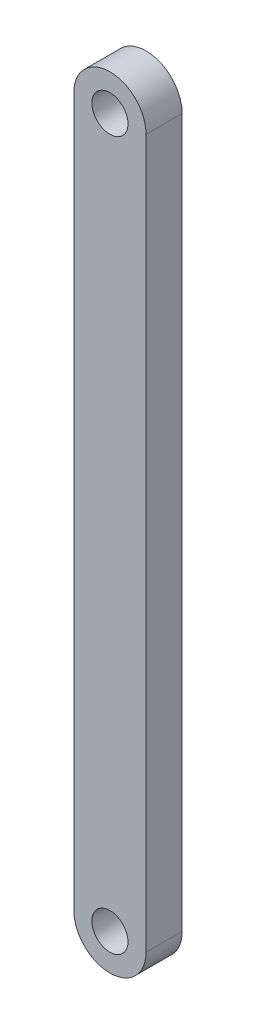
SolidWorks part; units mm, degrees
ref_plane "Alzado" through (0, 0, 0) normal (0, 0, 1) x (1, 0, 0)
ref_plane "Planta" through (0, 0, 0) normal (0, 1, 0) x (1, 0, 0)
ref_plane "Vista lateral" through (0, 0, 0) normal (1, 0, 0) x (0, 0, -1)
sketch "Croquis1" plane through (0, 0, 0) normal (0, 0, 1) x (1, 0, 0)
  line L0 (0, 0) -> (0, 117.69) construction
  line L1 (-6, 0) -> (-6, 117.69)
  line L2 (6, 0) -> (6, 117.69)
  arc A0 (-6, 0) -> (6, 0) centre (0, 0) ccw
  circle A1 centre (0, 0) radius 3
  arc A2 (6, 117.69) -> (-6, 117.69) centre (0, 117.69) ccw
  circle A3 centre (0, 117.69) radius 3
  dimension "D1" = 12
  dimension "D2" = 6
  dimension "D4" = 6
  dimension "D3" = 117.69
extrude "Saliente-Extruir1" add sketch "Croquis1" along normal blind 6
